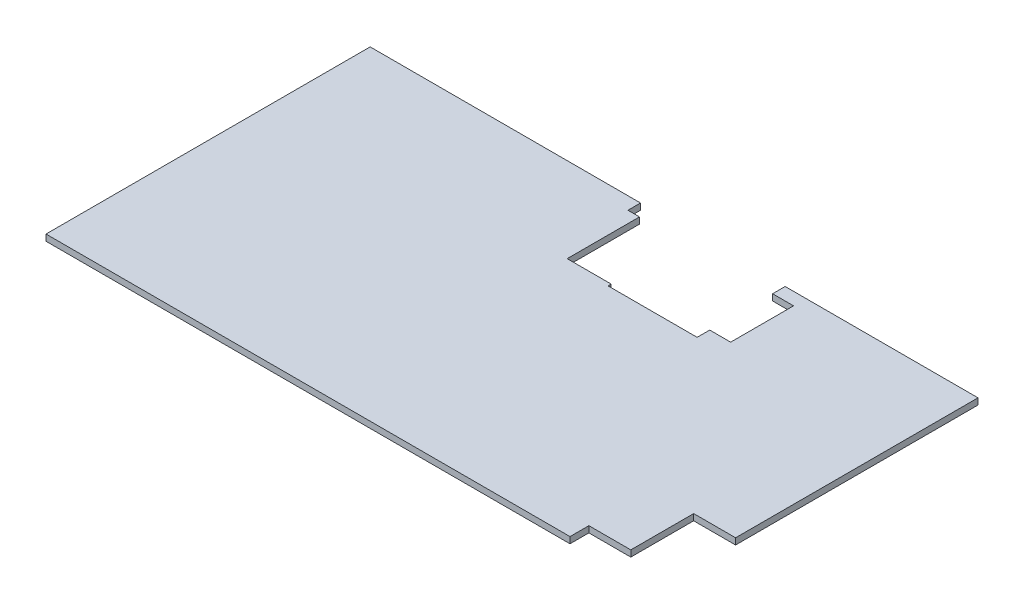
SolidWorks part; units mm, degrees
ref_plane "Front Plane" through (0, 0, 0) normal (0, 0, 1) x (1, 0, 0)
ref_plane "Top Plane" through (0, 0, 0) normal (0, 1, 0) x (1, 0, 0)
ref_plane "Right Plane" through (0, 0, 0) normal (1, 0, 0) x (0, 0, -1)
sketch "Sketch1" plane through (0, 0, 0) normal (0, 1, 0) x (1, 0, 0)
  line L1 (145, 77.325) -> (-145, 77.325)
  line L2 (145, 77.325) -> (145, -77.325)
  line L3 (145, -77.325) -> (-145, -77.325)
  line L4 (-145, 77.325) -> (-145, -77.325)
  line L5 (145, 77.325) -> (-145, -77.325) construction
  line L6 (145, -77.325) -> (-145, 77.325) construction
  point P0 (0, 0)
  dimension "D1" = 154.65
  dimension "D2" = 290
extrude "Boss-Extrude1" add sketch "Sketch1" along normal blind 3
sketch "Sketch2" plane through (0, 3, 0) normal (0, 1, 0) x (1, 0, 0)
  line L0 (145, 77.325) -> (53, 77.325)
  line L1 (-16, 77.325) -> (53, 77.325)
  line L2 (145, 77.325) -> (-145, 77.325) construction
  line L3 (-145, 77.325) -> (-16, 77.325)
  line L4 (-16, 77.325) -> (-16, 71.325)
  line L5 (-16, 71.325) -> (-10.5, 71.325)
  line L6 (19.5, 35.325) -> (19.5, 15.325)
  line L7 (19.5, 15.325) -> (39.5, 15.325)
  line L8 (39.5, 15.325) -> (39.5, 35.325)
  line L9 (53, 77.325) -> (53, 35.325)
  line L10 (53, 35.325) -> (39.5, 35.325)
  line L11 (-10.5, 71.325) -> (-10.5, 36.825)
  line L12 (-10.5, 36.825) -> (10.5, 36.825)
  line L13 (10.5, 36.825) -> (10.5, 35.325)
  line L14 (10.5, 35.325) -> (19.5, 35.325)
  line L15 (19.5, 35.325) -> (39.5, 35.325)
  line M4 (145, 77.325) -> (-145, 77.325)
  dimension "D1" = 92
  dimension "D2" = 129
  dimension "D3" = 5.5
  dimension "D4" = 20
  dimension "D5" = 20
  dimension "D6" = 42
  dimension "D7" = 6
  dimension "D8" = 21
  dimension "D9" = 20
  dimension "D10" = 34.5
  dimension "D11" = 9
extrude "Cut-Extrude1" cut sketch "Sketch2" against normal through all contours L13 L14 L6 L7 L8 L10 L9 L4 L5 L11 L12 M4
sketch "Sketch3" plane through (0, 3, 0) normal (0, 1, 0) x (1, 0, 0)
  line L0 (53, 35.325) -> (53, 77.325)
  line L1 (53, 56.325) -> (63, 56.325)
  line L2 (63, 41.325) -> (63, 71.325)
  line L3 (63, 71.325) -> (53, 71.325)
  line L4 (63, 41.325) -> (53, 41.325)
  line L5 (53, 71.325) -> (53, 41.325)
  point P9 (63, 56.325)
  dimension "D1" = 10
  dimension "D2" = 30
extrude "Cut-Extrude2" cut sketch "Sketch3" against normal blind 3 contours L2 L3 L0 L1 | L4 L2 L1 L0
sketch "Sketch5" plane through (0, 0, 0) normal (0, -1, 0) x (-1, 0, 0)
  line L1 (-145, -77.325) -> (-105, -77.325)
  line L2 (-145, -77.325) -> (-145, -68.325)
  line L3 (-145, -68.325) -> (-105, -68.325)
  line L4 (-105, -77.325) -> (-105, -68.325)
  line L5 (-145, -77.325) -> (-105, -68.325) construction
  line L6 (-145, -68.325) -> (-105, -77.325) construction
  point P4 (-125, -72.825)
  dimension "D1" = 9
  dimension "D2" = 40
extrude "Cut-Extrude3" cut sketch "Sketch5" against normal blind 3
sketch "Sketch6" plane through (0, 3, 0) normal (0, 1, 0) x (1, 0, 0)
  line L1 (145, -68.325) -> (125, -68.325)
  line L2 (145, -68.325) -> (145, -38.325)
  line L3 (145, -38.325) -> (125, -38.325)
  line L4 (125, -68.325) -> (125, -38.325)
  line L5 (145, -68.325) -> (125, -38.325) construction
  line L6 (145, -38.325) -> (125, -68.325) construction
  point P4 (135, -53.325)
  dimension "D1" = 30
  dimension "D2" = 20
extrude "Cut-Extrude4" cut sketch "Sketch6" against normal blind 3
